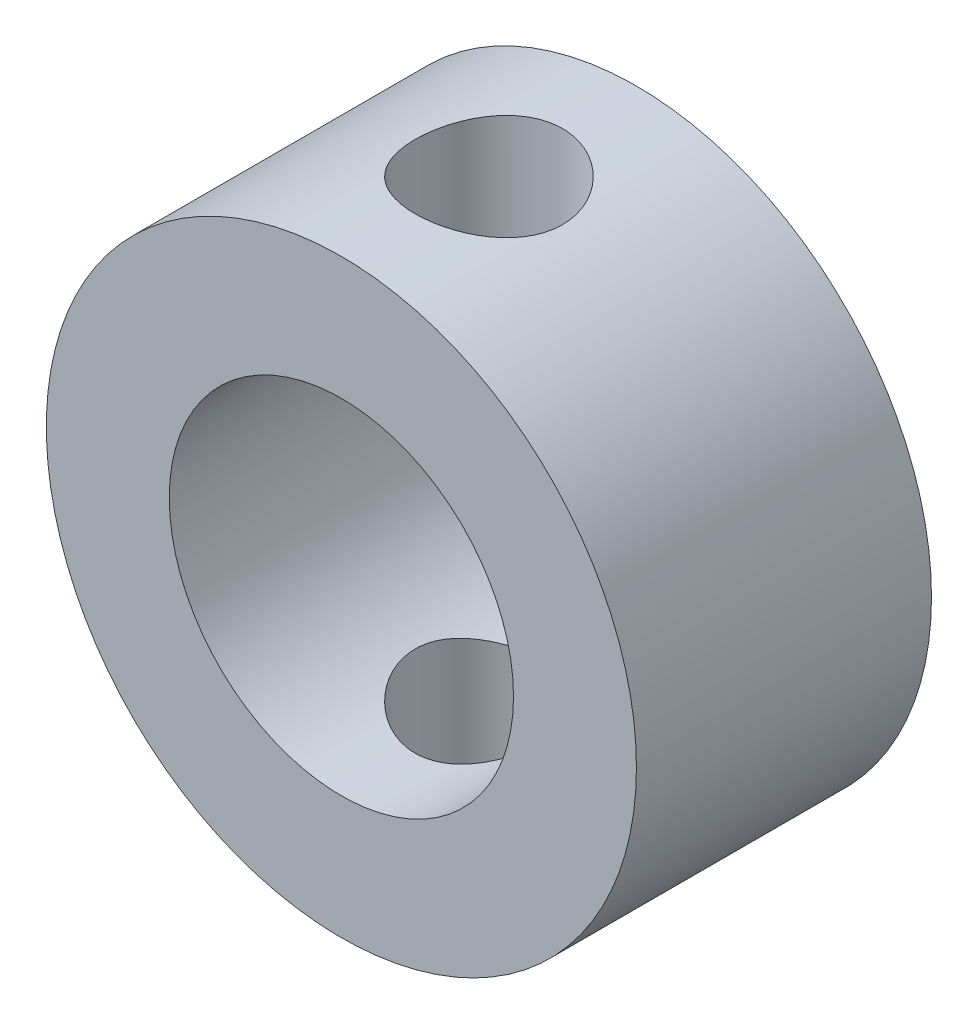
SolidWorks part; units mm, degrees
ref_plane "Ön Düzlem" through (0, 0, 0) normal (0, 0, 1) x (1, 0, 0)
ref_plane "Üst Düzlem" through (0, 0, 0) normal (0, 1, 0) x (1, 0, 0)
ref_plane "Sağ Düzlem" through (0, 0, 0) normal (1, 0, 0) x (0, 0, -1)
sketch "Sketch1" plane through (0, 0, 0) normal (0, 0, 1) x (1, 0, 0)
  circle A0 centre (0, 0) radius 7
  circle A1 centre (0, 0) radius 12
extrude "Boss-Extrude1" add sketch "Sketch1" along normal blind 12
sketch "Sketch2" plane through (0, 0, 0) normal (0, 1, 0) x (1, 0, 0)
  circle A0 centre (0, -6) radius 3
extrude "Cut-Extrude1" cut sketch "Sketch2" against normal through all and the other way through all
